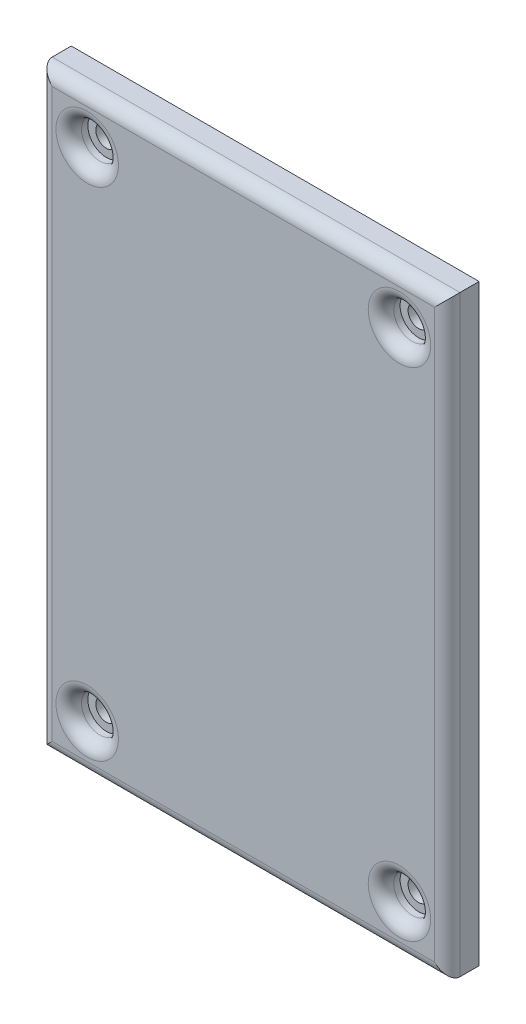
SolidWorks part; units mm, degrees
ref_plane "Ebene vorne" through (0, 0, 0) normal (0, 0, 1) x (1, 0, 0)
ref_plane "Ebene oben" through (0, 0, 0) normal (0, 1, 0) x (1, 0, 0)
ref_plane "Ebene rechts" through (0, 0, 0) normal (1, 0, 0) x (0, 0, -1)
sketch "Skizze1" plane through (0, 0, 0) normal (0, 0, 1) x (1, 0, 0)
  line L0 (0, 0) -> (-19.3803, 0) construction
  line L1 (-32, -46.5) -> (32, -46.5)
  line L2 (-32, -46.5) -> (-32, 46.5)
  line L3 (-32, 46.5) -> (32, 46.5)
  line L4 (32, -46.5) -> (32, 46.5)
  line L5 (-32, -46.5) -> (32, 46.5) construction
  line L6 (-32, 46.5) -> (32, -46.5) construction
  line L7 (-19.3803, 0) -> (0, 0) construction
  line L8 (0, 0) -> (0, 13.5211) construction
  circle A0 centre (-24.5, 39) radius 1.65
  circle A1 centre (24.5, 39) radius 1.65
  circle A2 centre (24.5, -39) radius 1.65
  circle A3 centre (-24.5, -39) radius 1.65
  point P0 (0, 0)
  dimension "D3" = 3.3
  dimension "D1" = 64
  dimension "D2" = 93
  dimension "D4" = 39
  dimension "D5" = 7.5
extrude "Aufsatz-Linear austragen2" add sketch "Skizze1" along normal blind 5
sketch "Skizze2" plane through (0, 0, 5) normal (0, 0, 1) x (1, 0, 0)
  line L0 (0, 0) -> (0, 8.2595) construction
  line L1 (11.4667, 0) -> (-11.4667, 0) construction
  circle A0 centre (-24.5, 39) radius 2.9
  circle A1 centre (24.5, 39) radius 2.9
  circle A2 centre (24.5, -39) radius 2.9
  circle A3 centre (-24.5, -39) radius 2.9
  dimension "D1" = 5.8
extrude "Schnitt-Linear austragen1" cut sketch "Skizze2" against normal blind 3
fillet "Verrundung1" radius 2 8 edges at (0, -46.5, 5) (-32, 0, 5) (0, 46.5, 5) (32, 0, 5) (-21.6, 39, 5) (21.6, 39, 5) (27.4, -39, 5) (-27.4, -39, 5)
